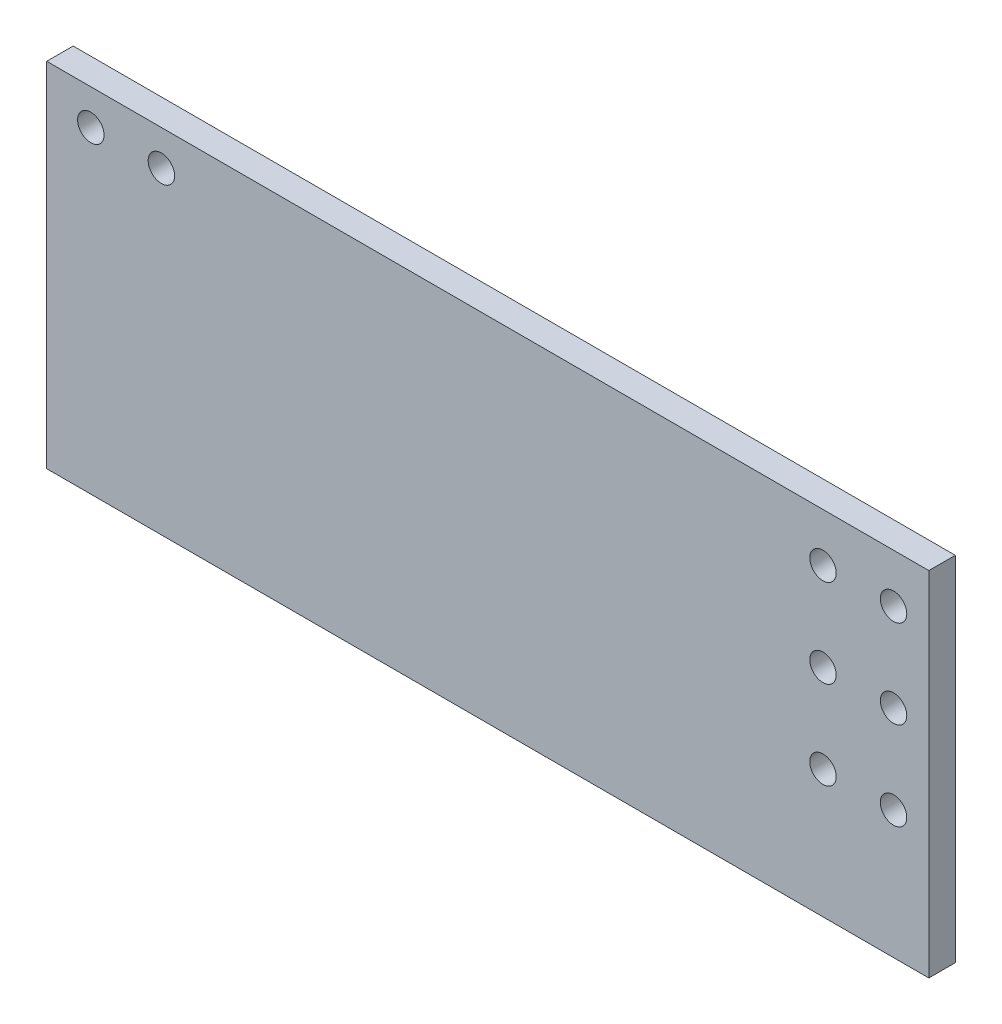
SolidWorks part; units mm, degrees
ref_plane "Front Plane" through (0, 0, 0) normal (0, 0, 1) x (1, 0, 0)
ref_plane "Top Plane" through (0, 0, 0) normal (0, 1, 0) x (1, 0, 0)
ref_plane "Right Plane" through (0, 0, 0) normal (1, 0, 0) x (0, 0, -1)
sketch "Sketch1" plane through (0, 0, 0) normal (0, 0, 1) x (1, 0, 0)
  line L0 (-50, 0) -> (49950, 0) construction
  line L1 (-50, -27.5) -> (50, -27.5)
  line L2 (-50, -27.5) -> (-50, 27.5)
  line L3 (-50, 27.5) -> (50, 27.5)
  line L4 (50, -27.5) -> (50, 27.5)
  line L5 (-50, -27.5) -> (50, 27.5) construction
  line L6 (-50, 27.5) -> (50, -27.5) construction
  circle A0 centre (38, 10) radius 1.5
  circle A1 centre (46, 10) radius 1.5
  circle A2 centre (46, -10) radius 1.5
  circle A3 centre (38, -10) radius 1.5
  circle A4 centre (38, 0) radius 1.5
  circle A5 centre (46, 0) radius 1.5
  point P0 (0, 0)
  point P8 (-50, 0)
  dimension "D5" = 3
  dimension "D6" = 3
  dimension "D9" = 3
  dimension "D10" = 3
  dimension "D1" = 100
  dimension "D2" = 55
  dimension "D3" = 4
  dimension "D4" = 8
  dimension "D7" = 10
  dimension "D8" = 10
  dimension "D11" = 12
  dimension "D12" = 4
extrude "Boss-Extrude1" add sketch "Sketch1" along normal blind 3
sketch "Sketch2" plane through (0, 0, 3) normal (0, 0, 1) x (1, 0, 0)
  line L0 (50, -27.5) -> (50, 27.5) construction
  line L1 (-50, 27.5) -> (50, 27.5)
  line L2 (-50, 27.5) -> (-50, 15.5)
  line L3 (-50, 15.5) -> (50, 15.5)
  line L4 (50, 27.5) -> (50, 15.5)
  circle A0 centre (38, 10) radius 1.5 construction
  dimension "D1" = 5.5
extrude "Cut-Extrude1" cut sketch "Sketch2" against normal through all
sketch "Sketch3" plane through (0, 0, 3) normal (0, 0, 1) x (1, 0, 0)
  line L0 (50, -27.5) -> (50, 15.5) construction
  line L1 (50, -24.5) -> (-50, -24.5)
  line L2 (50, -24.5) -> (50, -27.5)
  line L3 (50, -27.5) -> (-50, -27.5)
  line L4 (-50, -24.5) -> (-50, -27.5)
  dimension "D1" = 3
extrude "Cut-Extrude2" cut sketch "Sketch3" against normal through all
sketch "Sketch4" plane through (0, 0, 3) normal (0, 0, 1) x (1, 0, 0)
  line L0 (-50, 11.5) -> (50, 11.5) construction
  line L1 (-50, 15.5) -> (-50, -24.5) construction
  line L2 (50, -24.5) -> (50, 15.5) construction
  line L3 (-50, 15.5) -> (50, 15.5) construction
  circle A0 centre (-45, 11.5) radius 1.5
  circle A1 centre (-37, 11.5) radius 1.5
  dimension "D2" = 3
  dimension "D3" = 3
  dimension "D1" = 4
  dimension "D4" = 8
  dimension "D5" = 5
extrude "Cut-Extrude3" cut sketch "Sketch4" against normal through all
